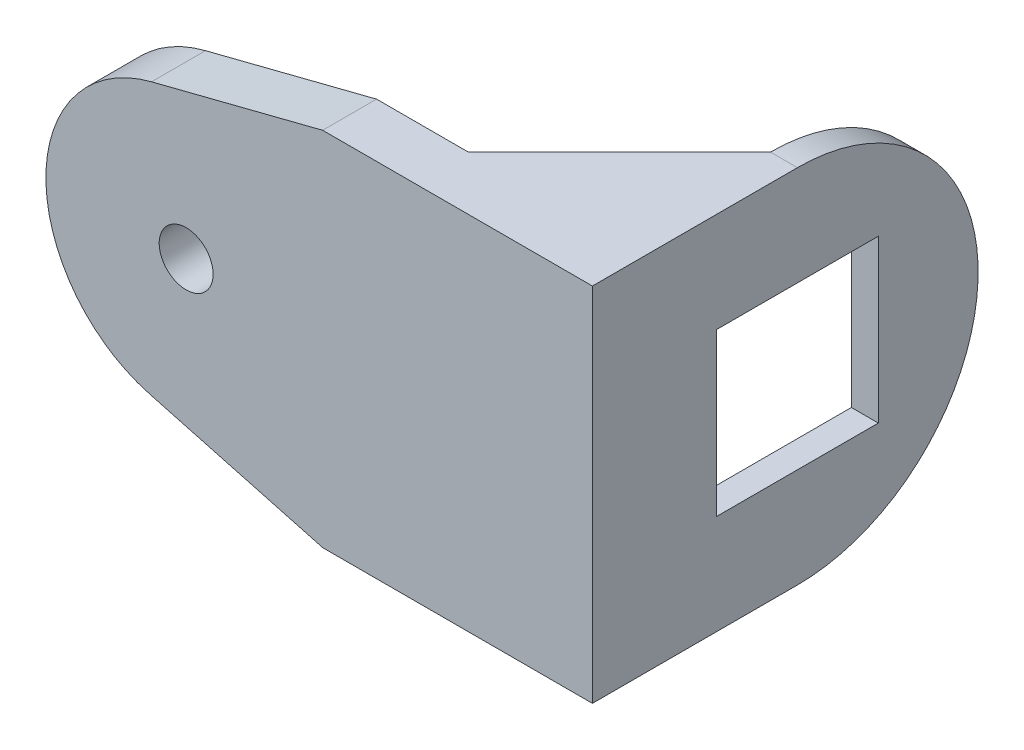
SolidWorks part; units mm, degrees
ref_plane "Front Plane" through (0, 0, 0) normal (0, 0, 1) x (1, 0, 0)
ref_plane "Top Plane" through (0, 0, 0) normal (0, 1, 0) x (1, 0, 0)
ref_plane "Right Plane" through (0, 0, 0) normal (1, 0, 0) x (0, 0, -1)
sketch "Sketch1" plane through (0, 0, 0) normal (0, 0, 1) x (1, 0, 0)
  line L0 (714.3872, 86.5406) -> (714.5095, 745.5406) construction
  line L1 (75.3049, -33.7249) -> (25.3049, -33.7249)
  line L2 (25.3049, -33.7249) -> (-6.7492, -25.1087)
  line L3 (-6.4172, 25.1956) -> (25.3049, 33.2751)
  line L4 (25.3049, 33.2751) -> (75.3049, 33.2751)
  line L5 (75.3049, 33.2751) -> (75.3049, -33.7249)
  arc A0 (-6.7492, -25.1087) -> (-6.4172, 25.1956) centre (0, 0) cw
  circle A1 centre (0, 0) radius 5
  dimension "D4" = 26
  dimension "D5" = 10
  dimension "D1" = 659
  dimension "D2" = 67
  dimension "D3" = 50
extrude "Boss-Extrude1" add sketch "Sketch1" along normal blind 10
sketch "Sketch2" plane through (75.3049, 0, 0) normal (1, 0, 0) x (0, 0, -1)
  line L0 (-10, 33.2751) -> (28, 33.2751)
  line L1 (28, -33.7249) -> (-10, -33.7249)
  line L2 (-10, -33.7249) -> (-10, 33.2751) construction
  line L4 (-10, -33.7249) -> (0, -33.7249) construction
  line L5 (0, 33.2751) -> (0, -33.7249)
  line L7 (43, -15.2249) -> (13, -15.2249)
  line L8 (43, -15.2249) -> (43, 14.7751)
  line L9 (43, 14.7751) -> (13, 14.7751)
  line L10 (13, -15.2249) -> (13, 14.7751)
  line L11 (43, -15.2249) -> (13, 14.7751) construction
  line L12 (43, 14.7751) -> (13, -15.2249) construction
  arc A0 (28, 33.2751) -> (28, -33.7249) centre (28, -0.2249) cw
  line M4 (0, -33.7249) -> (0, 33.2751)
  dimension "D1" = 38
  dimension "D2" = 30
extrude "Boss-Extrude2" add sketch "Sketch2" against normal blind 5 contours A0 L0 L1 L7 L10 L9 L8 M4
sketch "Sketch3" plane through (0, -33.7249, 0) normal (0, -1, 0) x (1, 0, 0)
  line L0 (70.3049, -28) -> (42.3049, 0)
  line L1 (25.3049, 0) -> (70.3049, 0) construction
  line L2 (42.3049, 0) -> (70.3049, 0)
  line L3 (70.3049, 0) -> (70.3049, -28)
  dimension "D1" = 45
extrude "Boss-Extrude3" add sketch "Sketch3" against normal blind 5
ref_plane "Plane1" through (0, -0.2249, 0) normal (0, 1, 0) x (1, 0, 0)
mirror "Mirror1" about plane through (0, -0.2249, 0) normal (0, 1, 0) of "Boss-Extrude3"
